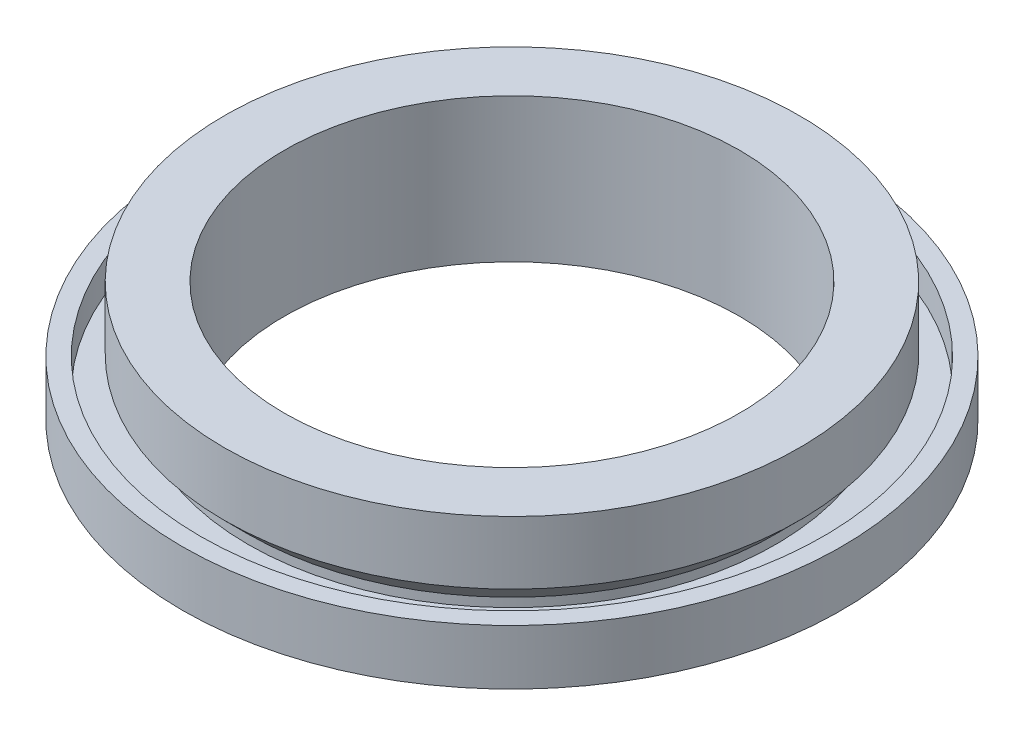
SolidWorks part; units mm, degrees
ref_plane "Front Plane" through (0, 0, 0) normal (0, 0, 1) x (1, 0, 0)
ref_plane "Top Plane" through (0, 0, 0) normal (0, 1, 0) x (1, 0, 0)
ref_plane "Right Plane" through (0, 0, 0) normal (1, 0, 0) x (0, 0, -1)
sketch "Sketch1" plane through (0, 0, 0) normal (0, 0, 1) x (1, 0, 0)
  line L3 (0, 74.5729) -> (0, 0) construction
sketch "Sketch2" plane through (0, 0, 0) normal (0, 0, 1) x (1, 0, 0)
  line L1 (-22, 4) -> (-22, 4.75)
  line L2 (-24, 6.75) -> (-24, 12)
  line L3 (-24, 12) -> (-19, 12)
  line L4 (-26, 4) -> (-22, 4)
  line L5 (-26, 4) -> (-26, 6.6)
  line L6 (-26, 6.6) -> (-27.5, 6.6)
  line L7 (-27.5, 6.6) -> (-27.5, 2)
  line L8 (-19, 12) -> (-19, 0)
  line L9 (-24, 6.75) -> (-22, 4.75)
  line L11 (-19, 0) -> (-23.75, 0)
  line L12 (-27.5, 2) -> (-23.75, 2)
  line L13 (-23.75, 2) -> (-23.75, 0)
  dimension "D1" = 5
  dimension "D2" = 0.75
  dimension "D3" = 2.75
  dimension "D4" = 12
  dimension "D5" = 4.6
  dimension "D6" = 1.5
  dimension "D7" = 4
  dimension "D8" = 3.5
  dimension "D9" = 4.75
  dimension "D10" = 2
  dimension "D11" = 2
  dimension "D12" = 19
revolve "Revolve1" add sketch "Sketch2" angle 360 about L3
fillet "Fillet1" radius 1 1 edges at (0, 2, 23.75)
